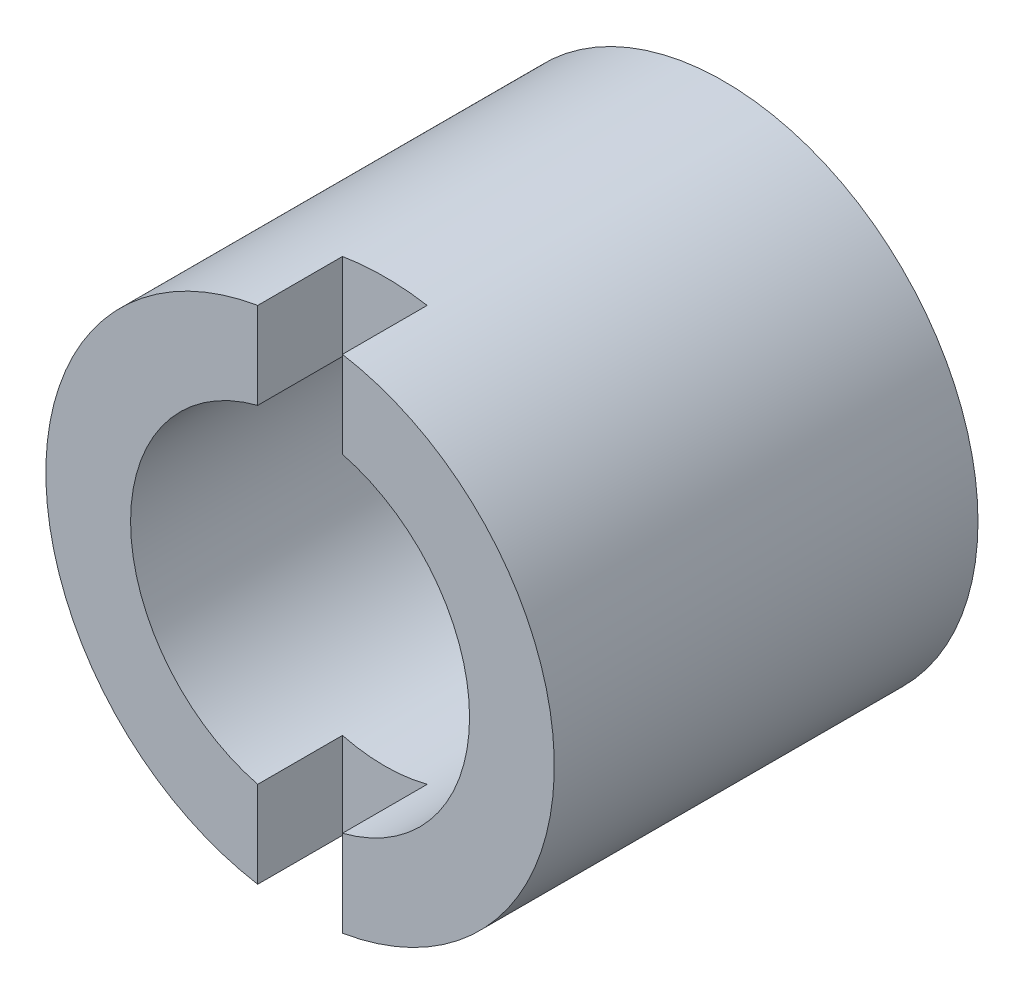
SolidWorks part; units mm, degrees
ref_plane "Front Plane" through (0, 0, 0) normal (0, 0, 1) x (1, 0, 0)
ref_plane "Top Plane" through (0, 0, 0) normal (0, 1, 0) x (1, 0, 0)
ref_plane "Right Plane" through (0, 0, 0) normal (1, 0, 0) x (0, 0, -1)
sketch "Sketch1" plane through (0, 0, 0) normal (0, 0, 1) x (1, 0, 0)
  circle A0 centre (0, 0) radius 6
extrude "Boss-Extrude1" add sketch "Sketch1" along normal blind 10
sketch "Sketch2" plane through (0, 0, 10) normal (0, 0, 1) x (1, 0, 0)
  circle A0 centre (0, 0) radius 4
extrude "Cut-Extrude1" cut sketch "Sketch2" against normal through all
sketch "Sketch3" plane through (0, 0, 0) normal (0, 1, 0) x (1, 0, 0)
  line L5 (-6, -10) -> (6, -10) construction
  line L11 (-1, -8) -> (1, -8)
  line L12 (1, -8) -> (1, -10)
  line L13 (1, -10) -> (-1, -10)
  line L14 (-1, -8) -> (-1, -10)
extrude "Cut-Extrude4" cut sketch "Sketch3" against normal through all and the other way through all
